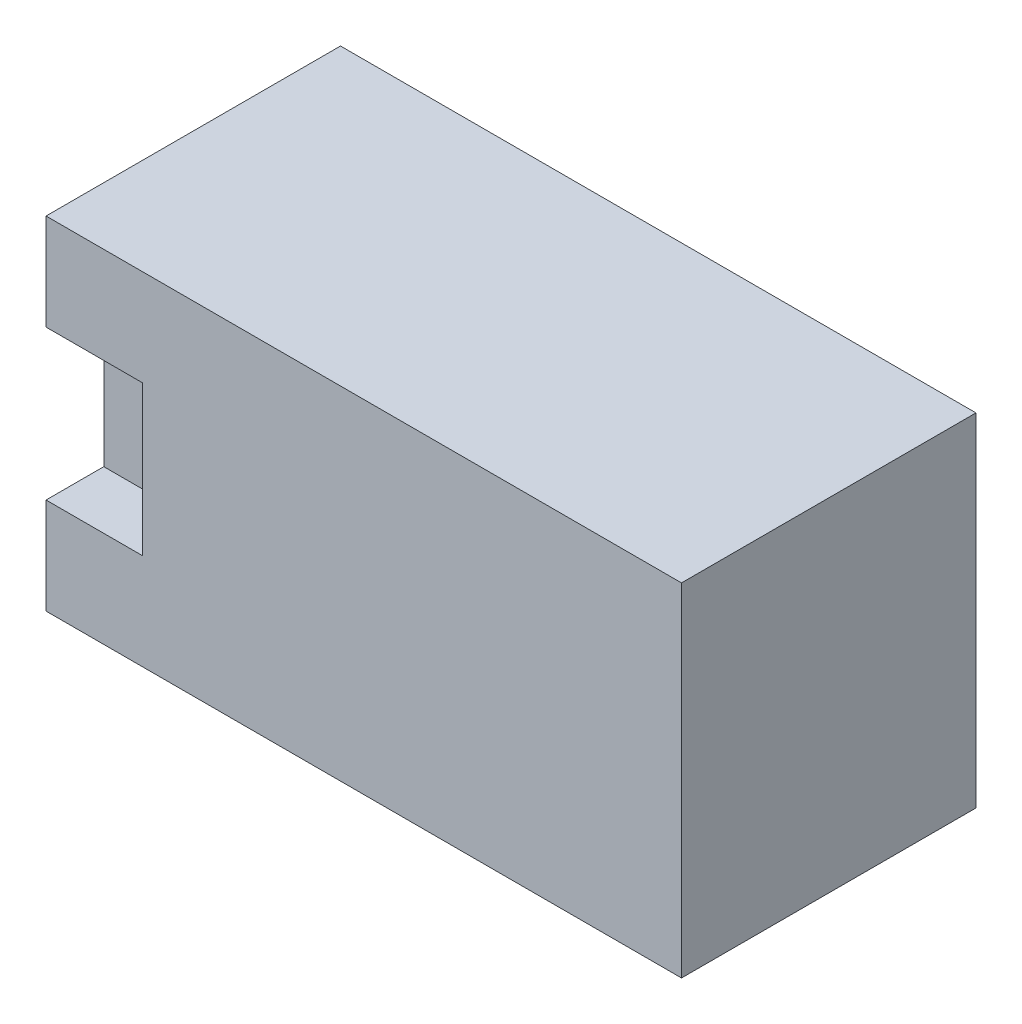
SolidWorks part; units mm, degrees
ref_plane "Front Plane" through (0, 0, 0) normal (0, 0, 1) x (1, 0, 0)
ref_plane "Top Plane" through (0, 0, 0) normal (0, 1, 0) x (1, 0, 0)
ref_plane "Right Plane" through (0, 0, 0) normal (1, 0, 0) x (0, 0, -1)
sketch "Sketch1" plane through (0, 0, 0) normal (0, 0, 1) x (1, 0, 0)
  line L1 (-83.9284, 14.7117) -> (-50.9084, 14.7117)
  line L2 (-83.9284, 14.7117) -> (-83.9284, -3.0683)
  line L3 (-83.9284, -3.0683) -> (-50.9084, -3.0683)
  line L4 (-50.9084, 14.7117) -> (-50.9084, -3.0683)
  dimension "D1" = 33.02
  dimension "D2" = 17.78
extrude "Boss-Extrude1" add sketch "Sketch1" along normal blind 15.3
sketch "Sketch2" plane through (-83.9284, 0, 0) normal (-1, 0, 0) x (0, 0, 1)
  line L1 (12.3, 9.7117) -> (15.3, 9.7117)
  line L2 (12.3, 9.7117) -> (12.3, 1.9317)
  line L3 (12.3, 1.9317) -> (15.3, 1.9317)
  line L4 (15.3, 9.7117) -> (15.3, 1.9317)
  line L5 (15.3, 14.7117) -> (15.3, -3.0683) construction
  line L7 (15.3, 14.7117) -> (0, 14.7117) construction
  line L8 (15.3, -3.0683) -> (0, -3.0683) construction
  dimension "D1" = 5
  dimension "D2" = 5
extrude "Cut-Extrude1" cut sketch "Sketch2" against normal blind 5
